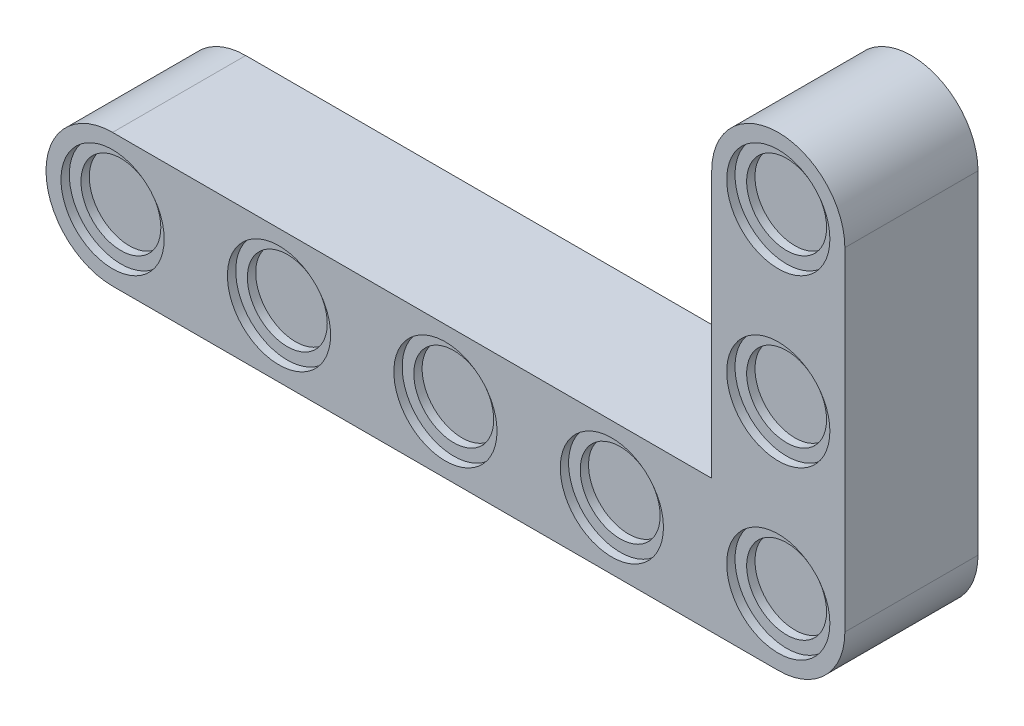
SolidWorks part; units mm, degrees
ref_plane "Front Plane" through (0, 0, 0) normal (0, 0, 1) x (1, 0, 0)
ref_plane "Top Plane" through (0, 0, 0) normal (0, 1, 0) x (1, 0, 0)
ref_plane "Right Plane" through (0, 0, 0) normal (1, 0, 0) x (0, 0, -1)
sketch "Sketch1" plane through (0, 0, 0) normal (0, 0, 1) x (1, 0, 0)
  line L0 (36, -2.6667) -> (36, -4)
  line L1 (0, 4) -> (36, 4)
  line L3 (0, -4) -> (40, -4)
  line L5 (-4, 4) -> (44, -4) construction
  line L6 (-4, -4) -> (44, 4) construction
  line L8 (36, 20) -> (36, 4)
  line L9 (36, -4) -> (40, -4)
  line L10 (44, 20) -> (44, 0)
  line L11 (36, 24) -> (44, -4) construction
  line L12 (36, -4) -> (44, 24) construction
  circle A0 centre (0, 0) radius 2.4
  circle A1 centre (0, 0) radius 3.1
  circle A2 centre (10, 0) radius 2.4
  circle A3 centre (10, 0) radius 3.1
  circle A4 centre (20, 0) radius 2.4
  circle A5 centre (20, 0) radius 3.1
  circle A6 centre (30, 0) radius 2.4
  circle A7 centre (30, 0) radius 3.1
  circle A8 centre (40, 0) radius 2.4
  circle A9 centre (40, 0) radius 3.1
  circle A10 centre (40, 10) radius 2.4
  circle A11 centre (40, 10) radius 3.1
  circle A12 centre (40, 20) radius 2.4
  circle A13 centre (40, 20) radius 3.1
  arc A14 (0, 4) -> (0, -4) centre (0, 0) ccw
  arc A15 (40, -4) -> (44, 0) centre (40, 0) ccw
  arc A16 (44, 20) -> (36, 20) centre (40, 20) ccw
  arc A17 (41.8428, 3.5502) -> (41.7064, 3.6177) centre (40, 0) ccw
  dimension "D1" = 4.8
  dimension "D2" = 6.2
  dimension "D5" = 8
  dimension "D6" = 48
  dimension "D7" = 8
  dimension "D3" = 5
  dimension "D4" = 3
extrude "Boss-Extrude1" add sketch "Sketch1" against normal blind 8 contours L3 A14 L1 L8 A16 L10 A15
sketch "Sketch2" plane through (0, 0, 0) normal (0, 0, 1) x (1, 0, 0)
  circle A0 centre (0, 0) radius 2.4
  dimension "D1" = 4.8
extrude "Cut-Extrude1" cut sketch "Sketch2" against normal blind 1
sketch "Sketch3" plane through (0, 0, 0) normal (0, 0, 1) x (1, 0, 0)
  circle A0 centre (0, 0) radius 3.1
  dimension "D1" = 6.2
extrude "Cut-Extrude2" cut sketch "Sketch3" against normal blind 0.5
pattern_linear "LPattern1" count 5 spacing 10 along (1, 0, 0) count 3 spacing 10 along (0, 1, 0) of "Cut-Extrude2", "Cut-Extrude1"
ref_plane "Plane1" through (0, 0, -4) normal (0, 0, 1) x (1, 0, 0)
mirror "Mirror1" about plane through (0, 0, -4) normal (0, 0, 1) of "LPattern1", "Cut-Extrude1", "Cut-Extrude2"
